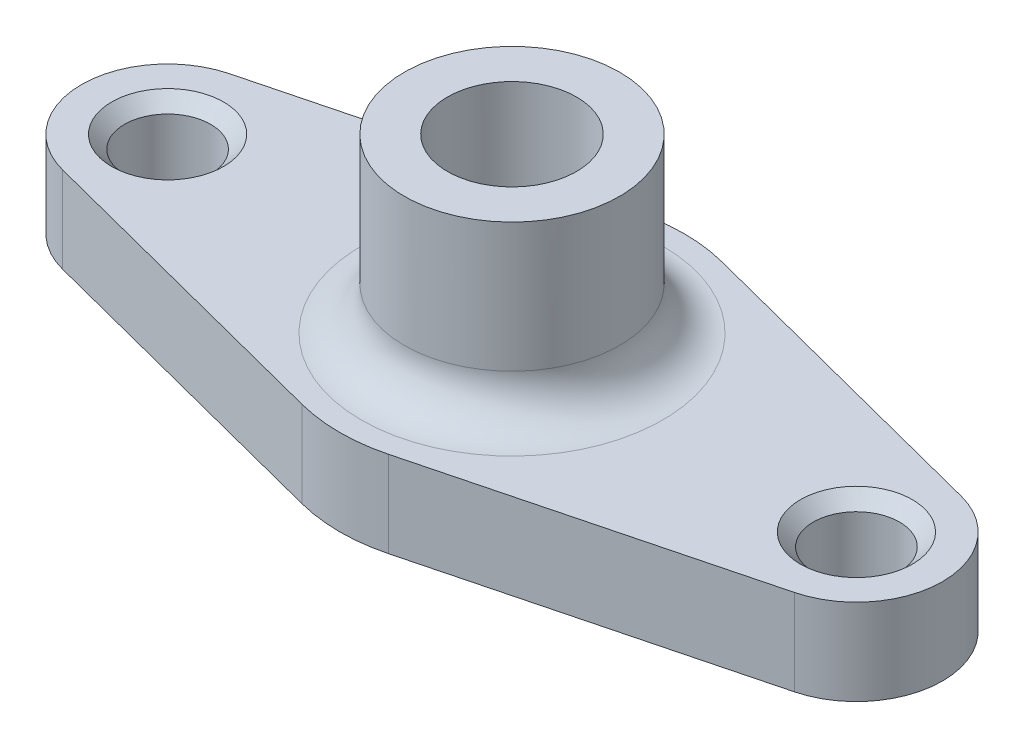
SolidWorks part; units mm, degrees
ref_plane "Front Plane" through (0, 0, 0) normal (0, 0, 1) x (1, 0, 0)
ref_plane "Top Plane" through (0, 0, 0) normal (0, 1, 0) x (1, 0, 0)
ref_plane "Right Plane" through (0, 0, 0) normal (1, 0, 0) x (0, 0, -1)
sketch "Эскиз2" [suppressed] plane through (0, 0, 0) normal (0, 1, 0) x (1, 0, 0)
  line L0 (0, 0) -> (0, -120)
  line L1 (0, -120) -> (60, -120)
  line L2 (60, -120) -> (60, 0)
  line L3 (30, 51.0451) -> (30, -98.9549) construction
  line L4 (97.9719, 0) -> (-22.0281, 0) construction
  arc A0 (60, 0) -> (0, 0) centre (30, 0) ccw
  circle A1 centre (30, 0) radius 20
  point P11 (84.2315, 0)
  dimension "D3" = 40
  dimension "D1" = 60
  dimension "D2" = 120
sketch "Sketch1" plane through (0, 0, 0) normal (0, 1, 0) x (1, 0, 0)
  line L0 (-49.3297, -6.5942) -> (-14.3297, 54.0276)
  line L1 (-14.3297, 54.0276) -> (20.6703, -6.5942)
  line L2 (20.6703, -6.5942) -> (-49.3297, -6.5942)
  line L3 (-14.3297, 54.0276) -> (-14.3297, -6.5942)
  line L4 (20.6703, -6.5942) -> (-31.8297, 23.7167)
  line L5 (-49.3297, -6.5942) -> (3.1703, 23.7167)
  point P3 (0, 0)
  point P7 (0, 0)
  point P8 (0, 0)
  dimension "D1" = 70
  dimension "D2" = 70
  dimension "D3" = 70
sketch "Sketch2" plane through (0, 0, 0) normal (0, 1, 0) x (1, 0, 0)
  line L1 (79.7356, 54.557) -> (149.7356, 54.557)
  line L2 (79.7356, 54.557) -> (79.7356, -15.443)
  line L3 (79.7356, -15.443) -> (149.7356, -15.443)
  line L4 (149.7356, 54.557) -> (149.7356, -15.443)
  circle A0 centre (114.7356, 19.557) radius 49.4975
  circle A1 centre (114.7356, 19.557) radius 35
  point P7 (0, 0)
  point P8 (0, 0)
  point P9 (0, 0)
  point P10 (-37.9298, 139.9355)
  point P11 (114.7356, 35.0629)
  dimension "D1" = 70
  dimension "D2" = 70
sketch "Sketch3" plane through (0, 0, 0) normal (0, 1, 0) x (1, 0, 0)
  line L0 (-55.8243, -118.0029) -> (-3.009, -92.2271)
  line L1 (-55.8243, -118.0029) -> (-41.8227, -60.9257)
  circle A0 centre (-9.7943, -60.9257) radius 32.0284
  circle A1 centre (-9.7943, -60.9257) radius 17.8777
sketch "Sketch4" plane through (0, 0, 0) normal (0, 1, 0) x (1, 0, 0)
  line L5 (122.6246, -92.0923) -> (73.1271, -42.5948)
  line L7 (73.1271, -92.0923) -> (122.6246, -42.5948)
  line L8 (66.0561, -85.0212) -> (115.5535, -35.5237)
  line L9 (115.5535, -99.1633) -> (66.0561, -49.6658)
  line L10 (80.1982, -99.1633) -> (129.6957, -49.6658)
  line L11 (129.6957, -85.0212) -> (80.1982, -35.5237)
  line L12 (73.1271, -92.0923) -> (122.6246, -42.5948) construction
  point P2 (0, 0)
  point P17 (97.8759, -67.3435)
  point P18 (97.8759, -67.3435)
  point P27 (246.9787, -66.0276)
  point P30 (0, 0)
  dimension "D1" = 10
  dimension "D2" = 10
sketch "Sketch5" plane through (0, 0, 0) normal (0, 1, 0) x (1, 0, 0)
  line L0 (-114.3162, 0) -> (114.3162, 0) construction
  line L1 (0, 50.3407) -> (0, -50.3407) construction
  line L2 (-80, -35.327) -> (-80, 35.327) construction
  line L3 (80, -35.327) -> (80, 35.327) construction
  line L4 (-10, 38.7298) -> (-85, 19.3649)
  line L5 (-10, -38.7298) -> (-85, -19.3649)
  line L6 (10, 38.7298) -> (85, 19.3649)
  line L7 (10, -38.7298) -> (85, -19.3649)
  circle A0 centre (0, 0) radius 15
  circle A1 centre (0, 0) radius 40
  circle A2 centre (-80, 0) radius 10
  circle A3 centre (80, 0) radius 10
  arc A4 (-85, -19.3649) -> (-85, 19.3649) centre (-80, 0) cw
  arc A5 (85, -19.3649) -> (85, 19.3649) centre (80, 0) ccw
  circle A7 centre (0, 0) radius 25
  dimension "D1" = 160
  dimension "D2" = 80
  dimension "D3" = 20
  dimension "D4" = 20
  dimension "D5" = 30
extrude "Boss-Extrude11" add sketch "Sketch5" along normal blind 20 contours A4 L5 A1 L4 A2 | L7 A5 L6 A1 A3 | A7 A0 | A1 A7
sketch "Sketch11" plane through (0, 0, 0) normal (0, -1, 0) x (1, 0, 0)
  circle A0 centre (0, 0) radius 25
  circle A1 centre (0, 0) radius 15
extrude "Boss-Extrude12" add sketch "Sketch11" against normal blind 60
chamfer "Chamfer3" distance 3 angle 45 1 edges at (-80, 20, 10)
fillet "Fillet2" radius 10 1 edges at (0, 20, 25)
chamfer "Chamfer4" distance 3 angle 45 1 edges at (80, 20, 10)
equation "\"D1@Эскиз2\"= \"D3@Эскиз2\" + 20"
equation "\"D2@Эскиз2\"= \"D1@Эскиз2\" * 2"
